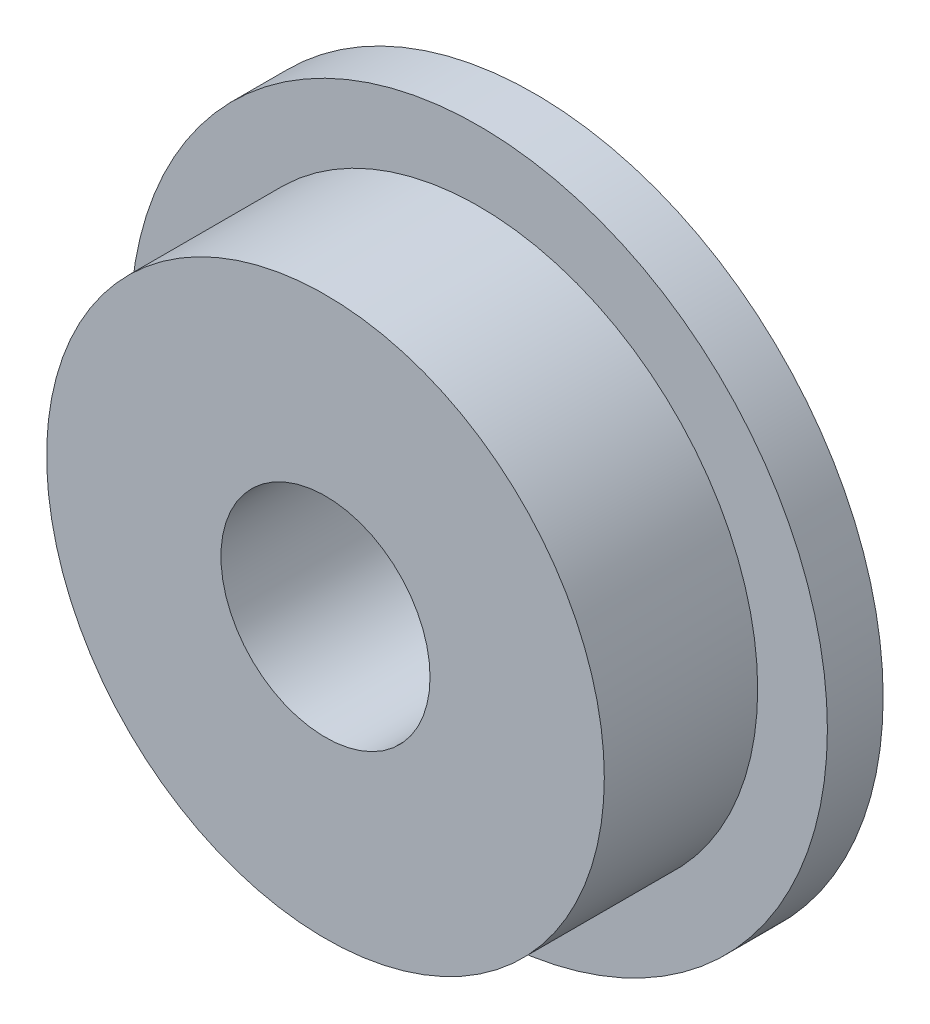
SolidWorks part; units mm, degrees
other "MotorBear"
material "Brass"
ref_plane "Front" through (0, 0, 0) normal (0, 0, 1) x (1, 0, 0)
ref_plane "Top" through (0, 0, 0) normal (0, 1, 0) x (1, 0, 0)
ref_plane "Right" through (0, 0, 0) normal (1, 0, 0) x (0, 0, -1)
sketch "Sketch1" plane through (0, 0, 0) normal (0, 0, 1) x (1, 0, 0)
  circle A0 centre (0, 0) radius 0.75
  circle A1 centre (0, 0) radius 2.5
  dimension "D1" = 1.5
  dimension "D2" = 5
extrude "Boss-Extrude1" add sketch "Sketch1" along normal blind 0.4
sketch "Sketch2" plane through (0, 0, 0.4) normal (0, 0, 1) x (1, 0, 0)
  circle A0 centre (0, 0) radius 0.75
  circle A1 centre (0, 0) radius 2
  circle A3 centre (0, 0) radius 0.75 construction
  dimension "D1" = 4
extrude "Boss-Extrude2" add sketch "Sketch2" along normal blind 1.1
